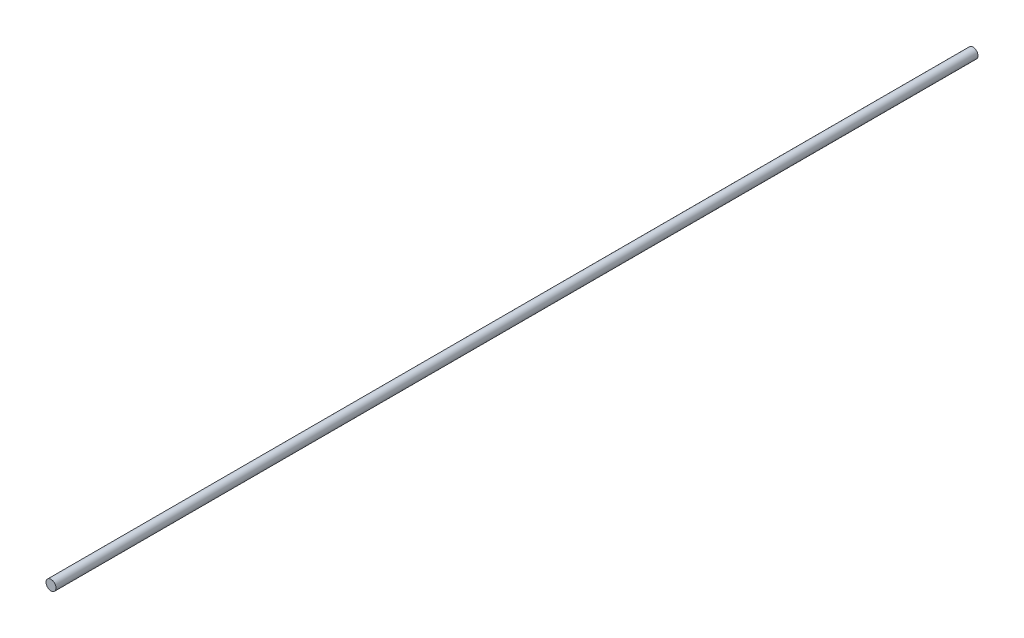
SolidWorks part; units mm, degrees
material "AISI 1020"
ref_plane "Front Plane" through (0, 0, 0) normal (0, 0, 1) x (1, 0, 0)
ref_plane "Top Plane" through (0, 0, 0) normal (0, 1, 0) x (1, 0, 0)
ref_plane "Right Plane" through (0, 0, 0) normal (1, 0, 0) x (0, 0, -1)
sketch "Sketch1" plane through (0, 0, 0) normal (0, 0, 1) x (1, 0, 0)
  circle A0 centre (0, 0) radius 7.9375
  dimension "D1" = 15.875
extrude "Boss-Extrude1" add sketch "Sketch1" along normal blind 2254.25
sketch "Sketch2" plane through (0, 0, 0) normal (0, 0, -1) x (-1, 0, 0)
  circle A0 centre (0, 0) radius 7.9375
extrude "Cut-Extrude1" cut sketch "Sketch2" against normal blind 539.75
sketch "Sketch3" plane through (0, 0, 2254.25) normal (0, 0, 1) x (1, 0, 0)
  circle A0 centre (0, 0) radius 7.9375
extrude "Cut-Extrude2" cut sketch "Sketch3" against normal blind 254
